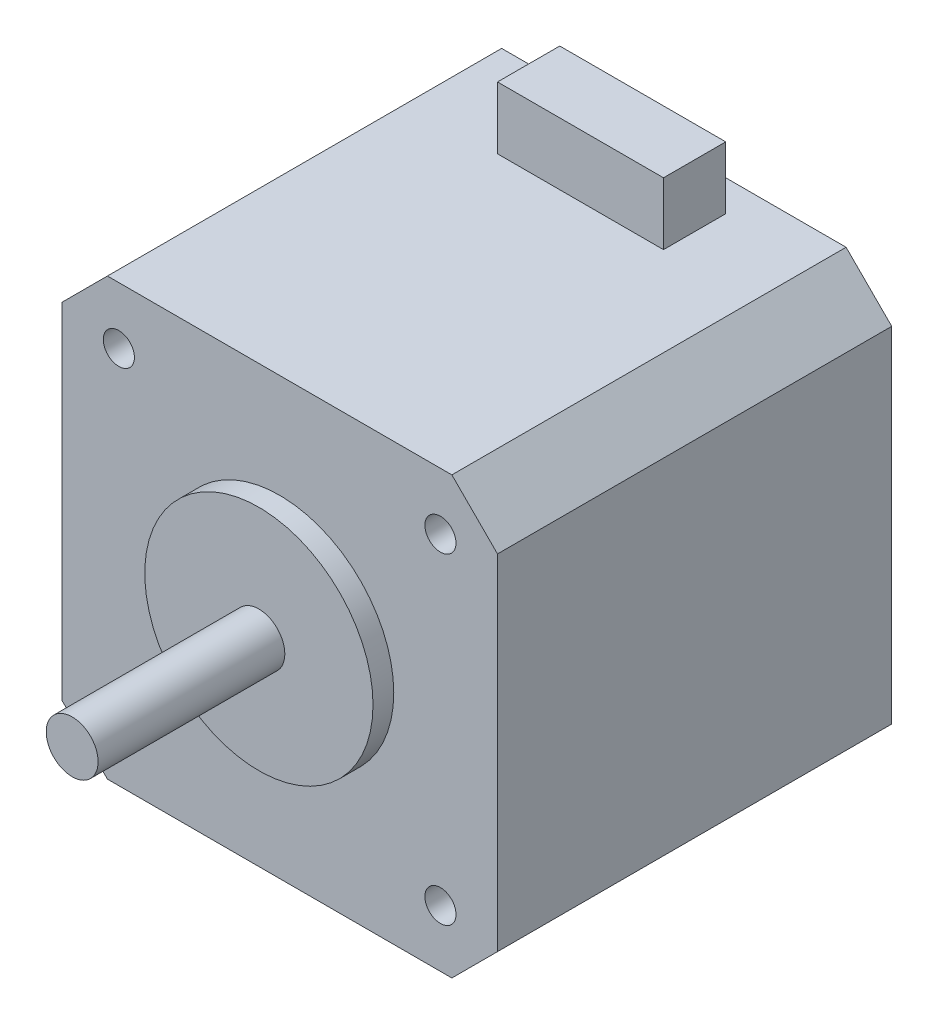
SolidWorks part; units mm, degrees
ref_plane "前视基准面" through (0, 0, 0) normal (0, 0, 1) x (1, 0, 0)
ref_plane "上视基准面" through (0, 0, 0) normal (0, 1, 0) x (1, 0, 0)
ref_plane "右视基准面" through (0, 0, 0) normal (1, 0, 0) x (0, 0, -1)
sketch "草图1" plane through (0, 0, 0) normal (0, 0, 1) x (1, 0, 0)
  line L0 (0, 0) -> (31.3879, 0) construction
  line L1 (0, 0) -> (0, 21.2989) construction
  line L2 (21, 0) -> (21, 16.6)
  line L3 (16.6, 21) -> (0, 21)
  line L4 (21, 16.6) -> (16.6, 21)
  line L5 (0, -21) -> (16.6, -21)
  line L6 (16.6, -21) -> (21, -16.6)
  line L7 (21, -16.6) -> (21, 0)
  line L8 (-21, 0) -> (-21, -16.6)
  line L9 (-21, -16.6) -> (-16.6, -21)
  line L10 (-16.6, -21) -> (0, -21)
  line L11 (0, 21) -> (-16.6, 21)
  line L12 (-16.6, 21) -> (-21, 16.6)
  line L13 (-21, 16.6) -> (-21, 0)
  circle A0 centre (15.5, 15.5) radius 1.5
  circle A1 centre (15.5, -15.5) radius 1.5
  circle A2 centre (-15.5, -15.5) radius 1.5
  circle A3 centre (-15.5, 15.5) radius 1.5
  point P5 (21, 21)
  point P32 (0, 0)
  dimension "D5" = 3
  dimension "D1" = 42
  dimension "D2" = 42
  dimension "D3" = 31
  dimension "D4" = 31
  dimension "D6" = 4
extrude "凸台-拉伸1" add sketch "草图1" along normal blind 38
sketch "草图2" plane through (0, 0, 38) normal (0, 0, 1) x (1, 0, 0)
  circle A0 centre (0, 0) radius 11
  dimension "D1" = 22
extrude "凸台-拉伸2" add sketch "草图2" along normal blind 2 contours A0
sketch "草图3" plane through (0, 0, 38) normal (0, 0, 1) x (1, 0, 0)
  circle A0 centre (0, 0) radius 2.5
  dimension "D1" = 5
extrude "凸台-拉伸3" add sketch "草图3" along normal blind 20
sketch "草图4" plane through (0, 21, 0) normal (0, 1, 0) x (1, 0, 0)
  line L0 (-8, -9) -> (8, -9)
  line L1 (16.6, 0) -> (-16.6, 0) construction
  line L2 (0, 0) -> (0, 3.5781) construction
  line L3 (-8, -9) -> (-8, -3)
  line L4 (-8, -3) -> (8, -3)
  line L5 (8, -3) -> (8, -9)
  dimension "D1" = 9
  dimension "D2" = 8
  dimension "D3" = 8
  dimension "D4" = 3
extrude "凸台-拉伸4" add sketch "草图4" along normal blind 6 contours L5 L0 L3 L4
